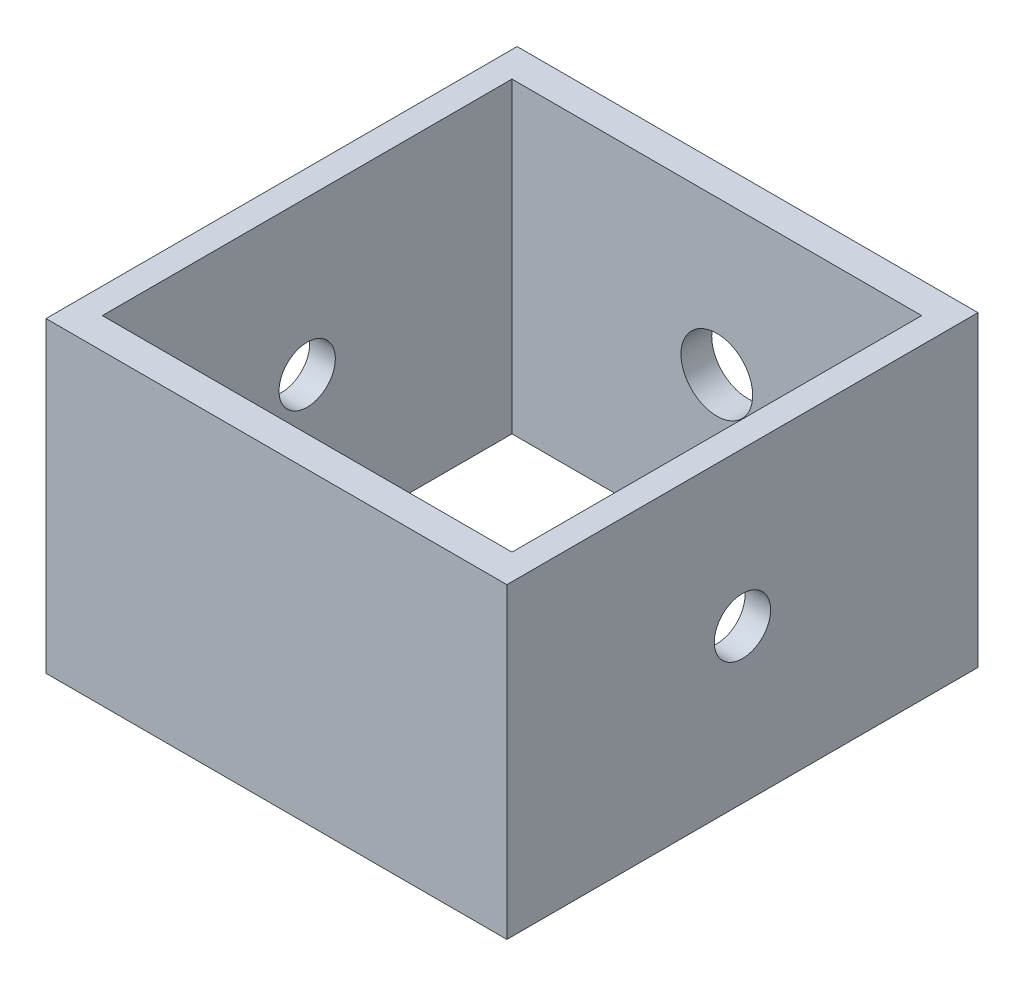
SolidWorks part; units mm, degrees
ref_plane "Front Plane" through (0, 0, 0) normal (0, 0, 1) x (1, 0, 0)
ref_plane "Top Plane" through (0, 0, 0) normal (0, 1, 0) x (1, 0, 0)
ref_plane "Right Plane" through (0, 0, 0) normal (1, 0, 0) x (0, 0, -1)
sketch "Sketch1" plane through (0, 0, 0) normal (0, 1, 0) x (1, 0, 0)
  line L1 (-22.5, -23) -> (22.5, -23)
  line L2 (-22.5, -23) -> (-22.5, 23)
  line L3 (-22.5, 23) -> (22.5, 23)
  line L4 (22.5, -23) -> (22.5, 23)
  line L5 (-22.5, -23) -> (22.5, 23) construction
  line L6 (-22.5, 23) -> (22.5, -23) construction
  point P0 (0, 0)
  dimension "D1" = 45
  dimension "D2" = 46
extrude "Boss-Extrude1" add sketch "Sketch1" along normal blind 30
sketch "Sketch2" plane through (0, 30, 0) normal (0, 1, 0) x (1, 0, 0)
  line L1 (-20, -20) -> (20, -20)
  line L2 (-20, -20) -> (-20, 20)
  line L3 (-20, 20) -> (20, 20)
  line L4 (20, -20) -> (20, 20)
  line L5 (-20, -20) -> (20, 20) construction
  line L6 (-20, 20) -> (20, -20) construction
  point P0 (0, 0)
  dimension "D1" = 40
  dimension "D2" = 40
sketch "Sketch3" plane through (0, 0, -23) normal (0, 0, -1) x (-1, 0, 0)
  line L0 (0, 21.1557) -> (0, -16.6176) construction
  line L1 (-22.5, 15) -> (22.5, 15) construction
  line L2 (-22.5, 30) -> (-22.5, 0) construction
  line L3 (22.5, 30) -> (22.5, 0) construction
  circle A0 centre (0, 15) radius 3.5
  dimension "D1" = 7
extrude "Cut-Extrude2" cut sketch "Sketch3" against normal blind 10
sketch "Sketch4" plane through (22.5, 0, 0) normal (1, 0, 0) x (0, 0, -1)
  line L0 (-23, 15) -> (23, 15) construction
  line L1 (-23, 30) -> (-23, 0) construction
  line L2 (23, 30) -> (23, 0) construction
  line L3 (0, 0) -> (0, 30) construction
  line L4 (-23, 30) -> (23, 30) construction
  circle A0 centre (0, 15) radius 2.75
  dimension "D1" = 5.5
extrude "Cut-Extrude3" cut sketch "Sketch4" against normal through all
extrude "Cut-Extrude4" cut sketch "Sketch2" against normal through all
